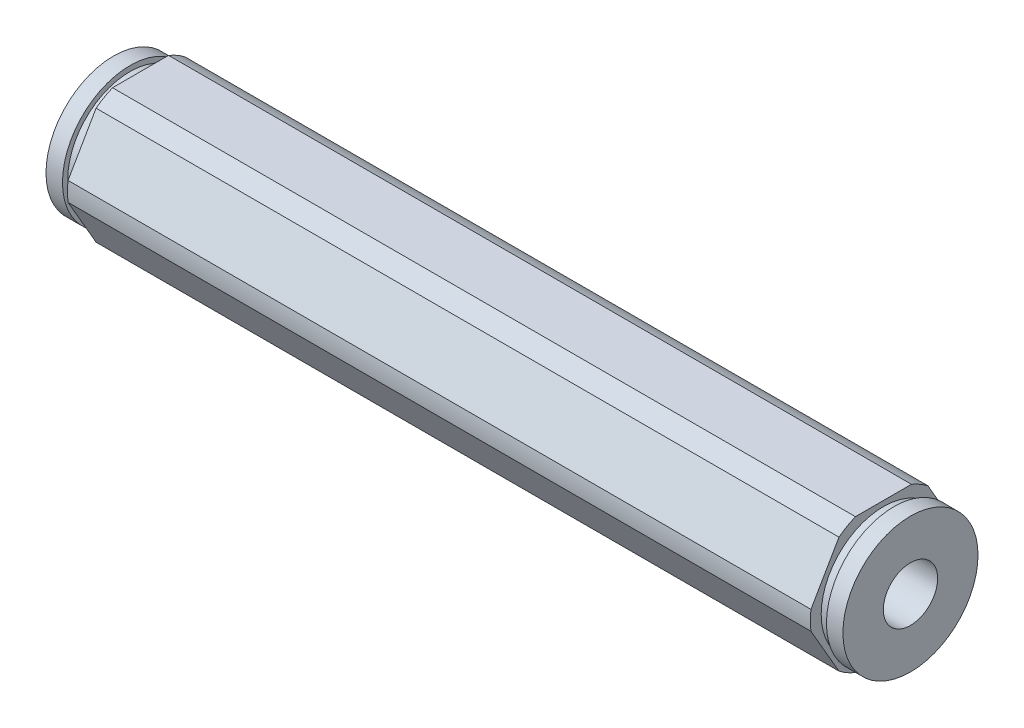
SolidWorks part; units mm, degrees
material "7075-T6 (SN)"
ref_plane "Front Plane" through (0, 0, 0) normal (0, 0, 1) x (1, 0, 0)
ref_plane "Top Plane" through (0, 0, 0) normal (0, 1, 0) x (1, 0, 0)
ref_plane "Right Plane" through (0, 0, 0) normal (1, 0, 0) x (0, 0, -1)
sketch "Sketch1" plane through (0, 0, 0) normal (1, 0, 0) x (0, 0, -1)
  line L1 (7.3323, 0) -> (3.6662, 6.35)
  line L2 (3.6662, 6.35) -> (-3.6662, 6.35)
  line L3 (-3.6662, 6.35) -> (-7.3323, 0)
  line L4 (-7.3323, 0) -> (-3.6662, -6.35)
  line L5 (-3.6662, -6.35) -> (3.6662, -6.35)
  line L6 (3.6662, -6.35) -> (7.3323, 0)
  circle A0 centre (0, 0) radius 6.35 construction
  dimension "D1" = 12.7
extrude "Boss-Extrude1" add sketch "Sketch1" along normal mid plane 74.93
sketch "Sketch2" plane through (0, 0, 0) normal (0, 1, 0) x (1, 0, 0)
  line L0 (34.925, -5.8547) -> (35.9156, -5.8547)
  line L1 (35.9156, -5.8547) -> (35.9156, -6.35)
  line L2 (35.9156, -6.35) -> (37.465, -6.35)
  line L3 (37.465, -6.35) -> (37.465, -8.89)
  line L4 (37.465, -8.89) -> (34.925, -8.89)
  line L5 (34.925, -8.89) -> (34.925, -5.8547)
  line L6 (0, 0) -> (49.5443, 0) construction
  dimension "D1" = 2.54
  dimension "D2" = 6.35
  dimension "D3" = 5.8547
  dimension "D4" = 2.54
  dimension "D5" = 0.9906
revolve "Cut-Revolve1" cut sketch "Sketch2" angle 360 about L6
mirror "Mirror1" about plane through (0, 0, 0) normal (1, 0, 0) of "Cut-Revolve1"
sketch "Sketch3" plane through (37.465, 0, 0) normal (1, 0, 0) x (0, 0, -1)
  circle A0 centre (0, 0) radius 6.875
  circle A1 centre (0, 0) radius 7.3323
  circle A2 centre (0, 0) radius 2.5527
  dimension "D1" = 13.75
  dimension "D2" = 5.1054
extrude "Cut-Extrude1" cut sketch "Sketch3" against normal through all contours A2 | A1 A0
